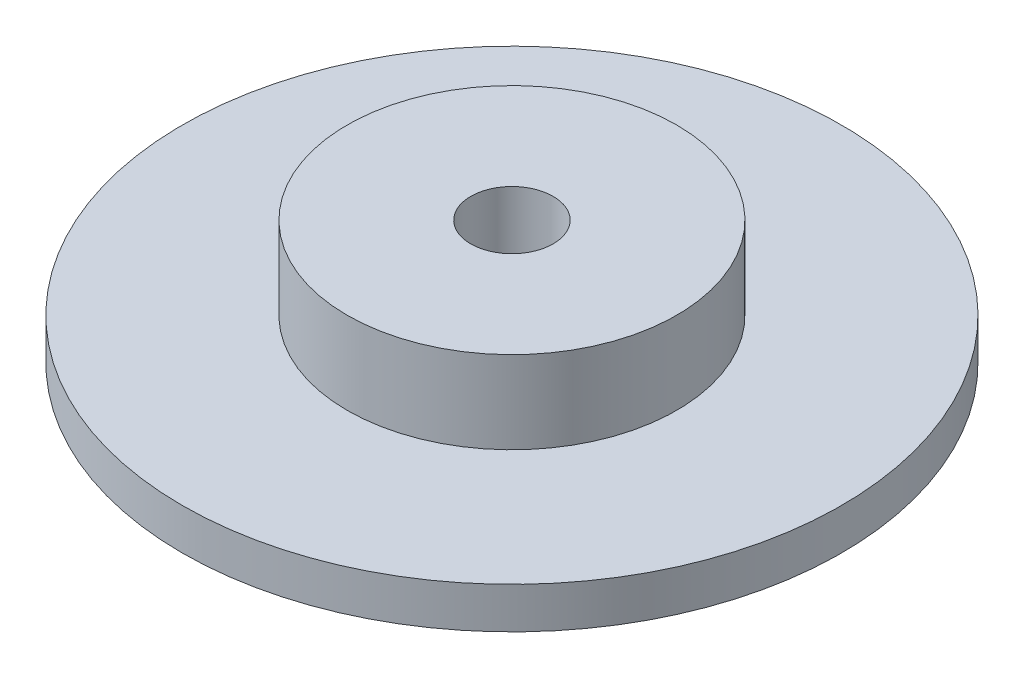
SolidWorks part; units mm, degrees
material "1023 Carbon Steel Sheet (SS)"
ref_plane "Front Plane" through (0, 0, 0) normal (0, 0, 1) x (1, 0, 0)
ref_plane "Top Plane" through (0, 0, 0) normal (0, 1, 0) x (1, 0, 0)
ref_plane "Right Plane" through (0, 0, 0) normal (1, 0, 0) x (0, 0, -1)
sketch "Sketch1" plane through (0, 0, 0) normal (0, 1, 0) x (1, 0, 0)
  circle A0 centre (0, 0) radius 25.4
  dimension "D1" = 50.8
extrude "Boss-Extrude1" add sketch "Sketch1" along normal blind 3.175 contours A0
sketch "Sketch2" plane through (0, 3.175, 0) normal (0, 1, 0) x (1, 0, 0)
  circle A0 centre (0, 0) radius 12.7
  dimension "D1" = 25.4
extrude "Boss-Extrude2" add sketch "Sketch2" along normal blind 6.35
sketch "Sketch3" plane through (0, 9.525, 0) normal (0, 1, 0) x (1, 0, 0)
  circle A0 centre (0, 0) radius 3.175
  dimension "D1" = 6.35
extrude "Cut-Extrude1" cut sketch "Sketch3" against normal through all
